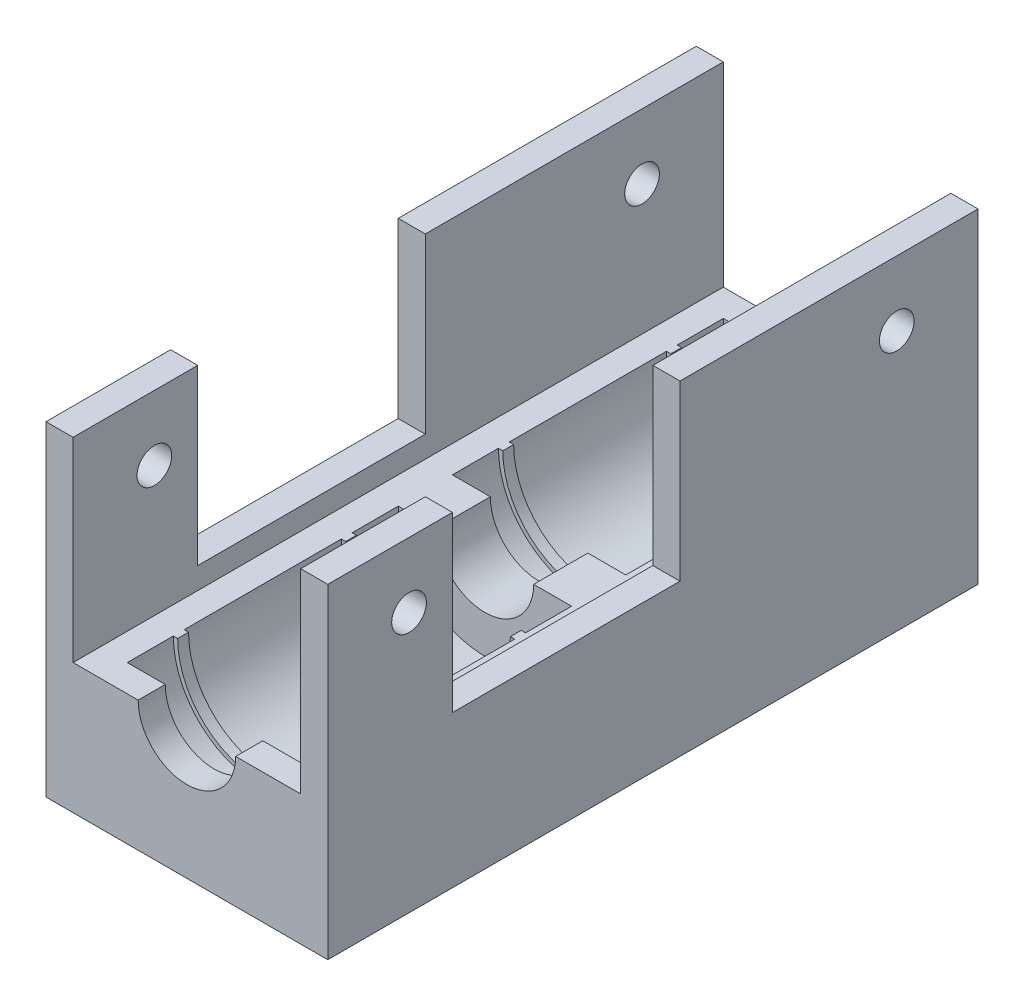
SolidWorks part; units mm, degrees
ref_plane "Front Plane" through (0, 0, 0) normal (0, 0, 1) x (1, 0, 0)
ref_plane "Top Plane" through (0, 0, 0) normal (0, 1, 0) x (1, 0, 0)
ref_plane "Right Plane" through (0, 0, 0) normal (1, 0, 0) x (0, 0, -1)
sketch "Sketch1" plane through (0, 0, 0) normal (0, 1, 0) x (1, 0, 0)
  line L1 (-10.5, -30) -> (10.5, -30)
  line L2 (-10.5, -30) -> (-10.5, 30)
  line L3 (-10.5, 30) -> (10.5, 30)
  line L4 (10.5, -30) -> (10.5, 30)
  line L5 (-10.5, -30) -> (10.5, 30) construction
  line L6 (-10.5, 30) -> (10.5, -30) construction
  point P0 (0, 0)
  dimension "D1" = 60
  dimension "D2" = 21
extrude "Boss-Extrude1" add sketch "Sketch1" along normal blind 12
sketch "Sketch2" plane through (0, 12, 0) normal (0, 1, 0) x (1, 0, 0)
  line L0 (0, -32.7836) -> (0, 32.1628) construction
  line L1 (0, 30) -> (4.5, 30)
  line L2 (10.5, 30) -> (-10.5, 30) construction
  line L3 (4.5, 30) -> (4.5, 27.5)
  line L4 (4.5, 27.5) -> (8, 27.5)
  line L5 (8, 27.5) -> (8, 23.25)
  line L6 (8, 23.25) -> (7.6, 23.25)
  line L7 (7.6, 23.25) -> (7.6, 22.25)
  line L8 (7.6, 22.25) -> (8, 22.25)
  line L9 (8, 22.25) -> (8, 7.75)
  line L10 (8, 7.75) -> (7.6, 7.75)
  line L11 (7.6, 7.75) -> (7.6, 6.75)
  line L12 (7.6, 6.75) -> (8, 6.75)
  line L13 (8, 6.75) -> (8, 2.5)
  line L14 (8, 2.5) -> (4.5, 2.5)
  line L15 (4.5, 2.5) -> (4.5, -2.5)
  line L16 (4.5, -2.5) -> (8, -2.5)
  line L17 (8, -2.5) -> (8, -6.75)
  line L18 (8, -6.75) -> (7.6, -6.75)
  line L19 (7.6, -6.75) -> (7.6, -7.75)
  line L20 (7.6, -7.75) -> (8, -7.75)
  line L21 (8, -7.75) -> (8, -22.25)
  line L22 (8, -22.25) -> (7.6, -22.25)
  line L23 (7.6, -22.25) -> (7.6, -23.25)
  line L24 (7.6, -23.25) -> (8, -23.25)
  line L25 (8, -23.25) -> (8, -27.5)
  line L26 (8, -27.5) -> (4.5, -27.5)
  line L27 (4.5, -27.5) -> (4.5, -30)
  line L28 (-10.5, -30) -> (10.5, -30) construction
  line L29 (4.5, -30) -> (0, -30)
  line L30 (0, -30) -> (0, 30)
  dimension "D1" = 9
  dimension "D2" = 16
  dimension "D3" = 25
  dimension "D4" = 2.5
  dimension "D5" = 1
  dimension "D6" = 0.4
  dimension "D7" = 16.5
revolve "Cut-Revolve1" cut sketch "Sketch2" angle 360 about L0
sketch "Sketch3" plane through (-10.5, 0, 0) normal (-1, 0, 0) x (0, 0, 1)
  line L0 (-30, 0) -> (-30, 30)
  line L1 (-30, 30) -> (-2.5, 30)
  line L2 (-2.5, 30) -> (-2.5, 14)
  line L3 (-30, 12) -> (30, 12) construction
  line L4 (-2.5, 14) -> (18.5, 14)
  line L5 (18.5, 14) -> (18.5, 30)
  line L6 (18.5, 30) -> (30, 30)
  line L7 (30, 30) -> (30, 0)
  line L8 (30, 0) -> (-30, 0)
  dimension "D1" = 27.5
  dimension "D2" = 11.5
  dimension "D3" = 18
  dimension "D4" = 2
extrude "Boss-Extrude2" add sketch "Sketch3" along normal blind 2.5
mirror "Mirror2" about plane through (0, 0, 0) normal (1, 0, 0) of "Boss-Extrude2"
sketch "Sketch7" plane through (-13, 0, 0) normal (-1, 0, 0) x (0, 0, 1)
  line L0 (30, 24) -> (22.5, 24) construction
  line L1 (30, 0) -> (30, 30) construction
  line L2 (22.5, 24) -> (-22.5, 24) construction
  line L3 (-22.5, 24) -> (-30, 24) construction
  line L4 (-30, 30) -> (-30, 0) construction
  circle A0 centre (22.5, 24) radius 1.6
  circle A1 centre (-22.5, 24) radius 1.6
  dimension "D1" = 3.2
  dimension "D2" = 12
  dimension "D3" = 45
extrude "Cut-Extrude2" cut sketch "Sketch7" against normal through all
